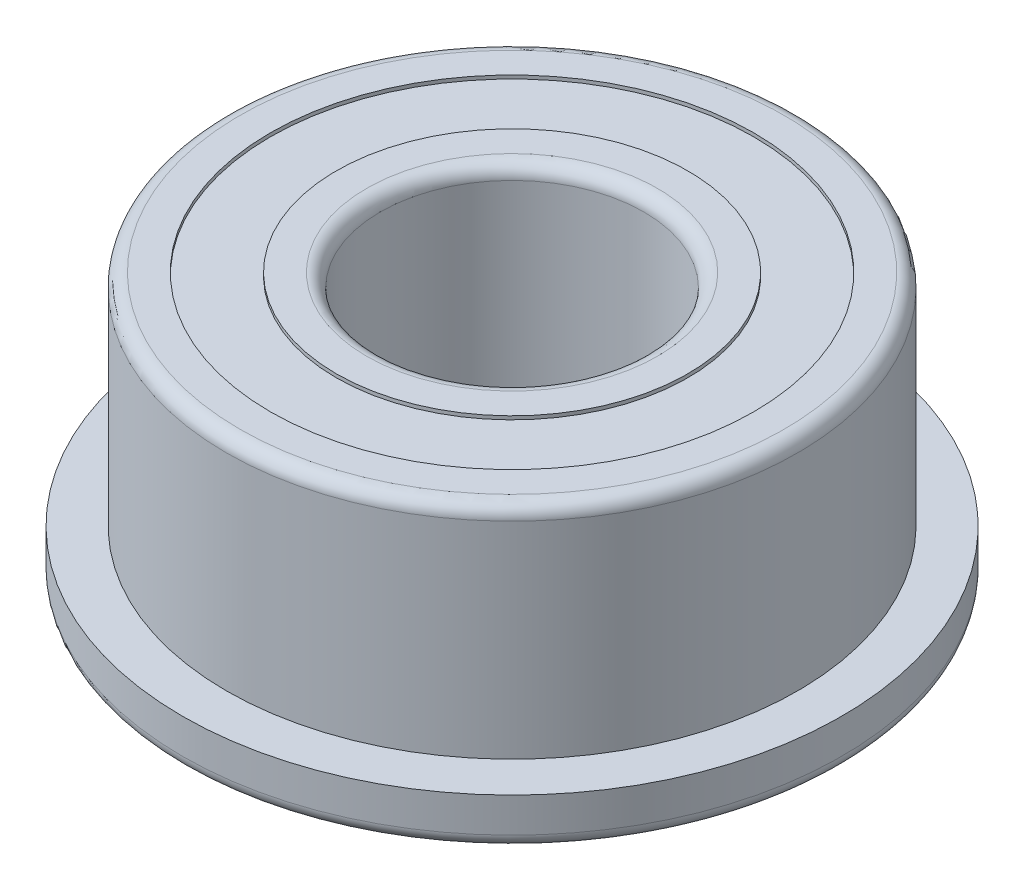
SolidWorks part; units mm, degrees
ref_plane "Front Plane" through (0, 0, 0) normal (0, 0, 1) x (1, 0, 0)
ref_plane "Top Plane" through (0, 0, 0) normal (0, 1, 0) x (1, 0, 0)
ref_plane "Right Plane" through (0, 0, 0) normal (1, 0, 0) x (0, 0, -1)
sketch "Sketch1" plane through (0, 0, 0) normal (0, 1, 0) x (1, 0, 0)
  circle A0 centre (0, 0) radius 7.5
  dimension "D1" = 15
extrude "Boss-Extrude1" add sketch "Sketch1" along normal blind 1.1
sketch "Sketch2" plane through (0, 1.1, 0) normal (0, 1, 0) x (1, 0, 0)
  circle A0 centre (0, 0) radius 6.5
  dimension "D1" = 13
extrude "Boss-Extrude2" add sketch "Sketch2" along normal blind 5
sketch "Sketch3" plane through (0, 6.1, 0) normal (0, 1, 0) x (1, 0, 0)
  circle A0 centre (0, 0) radius 3
  dimension "D1" = 6
extrude "Cut-Extrude1" cut sketch "Sketch3" against normal through all
sketch "Sketch4" plane through (0, 0, 0) normal (0, -1, 0) x (1, 0, 0)
  circle A0 centre (0, 0) radius 4
  circle A1 centre (0, 0) radius 6.5
  dimension "D1" = 13
  dimension "D2" = 8
extrude "Cut-Extrude2" cut sketch "Sketch4" against normal blind 0.08
sketch "Sketch5" plane through (0, 6.1, 0) normal (0, 1, 0) x (1, 0, 0)
  circle A0 centre (0, 0) radius 4
  circle A1 centre (0, 0) radius 5.5
  dimension "D1" = 11
  dimension "D2" = 8
extrude "Cut-Extrude3" cut sketch "Sketch5" against normal blind 0.08
fillet "Fillet1" radius 0.31 4 edges at (0, 0, 3) (0, 0, 7.5) (0, 6.1, 6.5) (0, 6.1, 3)
